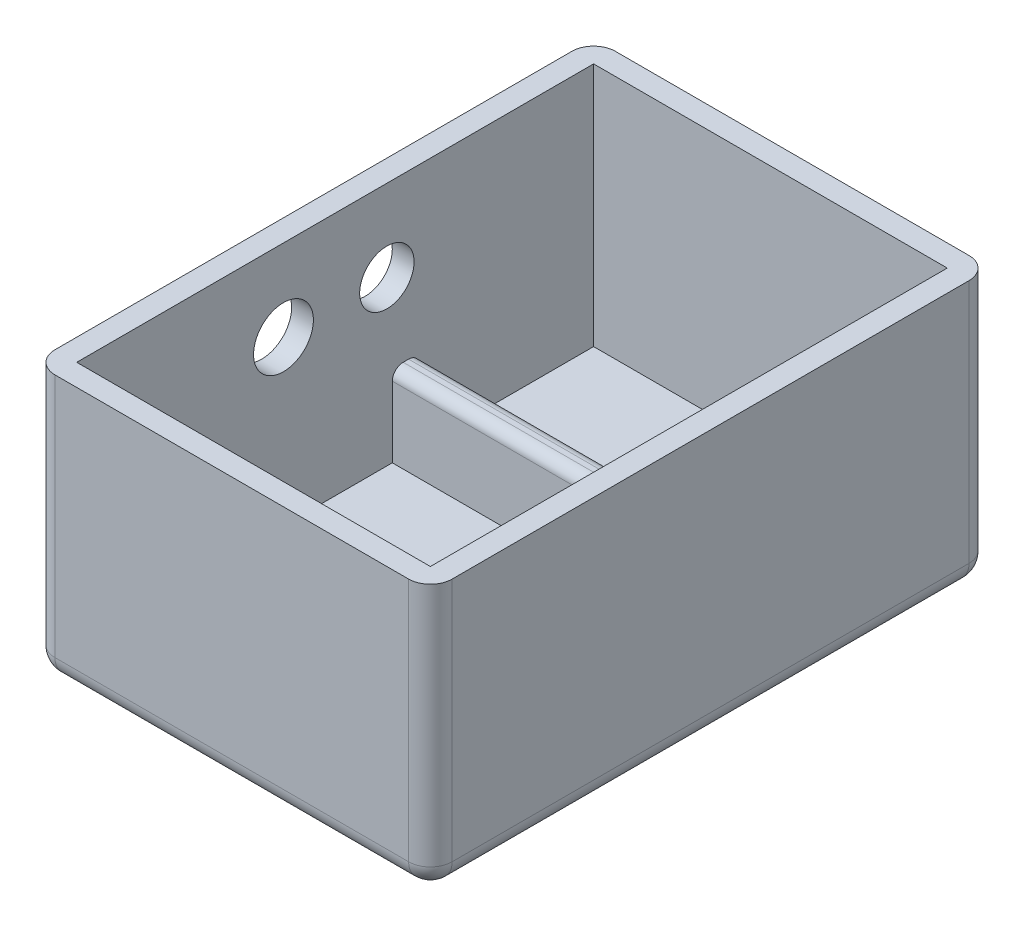
SolidWorks part; units mm, degrees
ref_plane "Front Plane" through (0, 0, 0) normal (0, 0, 1) x (1, 0, 0)
ref_plane "Top Plane" through (0, 0, 0) normal (0, 1, 0) x (1, 0, 0)
ref_plane "Right Plane" through (0, 0, 0) normal (1, 0, 0) x (0, 0, -1)
sketch "Sketch1" plane through (0, 0, 0) normal (0, 1, 0) x (1, 0, 0)
  line L1 (-32.5, -47.5) -> (32.5, -47.5)
  line L2 (-32.5, -47.5) -> (-32.5, 47.5)
  line L3 (-32.5, 47.5) -> (32.5, 47.5)
  line L4 (32.5, -47.5) -> (32.5, 47.5)
  line L5 (-32.5, -47.5) -> (32.5, 47.5) construction
  line L6 (-32.5, 47.5) -> (32.5, -47.5) construction
  point P0 (0, 0)
  dimension "D1" = 95
  dimension "D2" = 65
extrude "Boss-Extrude1" add sketch "Sketch1" along normal blind 45
shell "Shell4" thickness 4
sketch "Sketch3" plane through (0, 0, 0) normal (0, 1, 0) x (1, 0, 0)
  line L0 (-32.5, 47.5) -> (-32.5, -47.5) construction
  line L1 (-32.5, 15.5) -> (32.5, 15.5)
  line L2 (-32.5, 15.5) -> (-32.5, 10.5)
  line L3 (-32.5, 10.5) -> (32.5, 10.5)
  line L4 (32.5, 15.5) -> (32.5, 10.5)
  line L5 (32.5, -47.5) -> (32.5, 47.5) construction
  line L6 (-32.5, -47.5) -> (32.5, -47.5) construction
  dimension "D1" = 58
  dimension "D2" = 5
extrude "Boss-Extrude3" add sketch "Sketch3" along normal blind 15
sketch "Sketch4" plane through (-32.5, 0, 0) normal (1, 0, 0) x (0, 0, -1)
  line L0 (-47.5, 30) -> (47.5, 30) construction
  line L1 (-47.5, 45) -> (-47.5, 0) construction
  line L2 (47.5, 45) -> (47.5, 0) construction
  line L3 (47.5, 45) -> (-47.5, 45) construction
  circle A0 centre (9.5, 30) radius 5
  circle A1 centre (-9.5, 30) radius 5.5
  point P12 (-10.7969, 30)
  point P13 (5.9574, 30)
  point P16 (14.3271, 30.8945)
  dimension "D2" = 10
  dimension "D3" = 11
  dimension "D1" = 15
  dimension "D4" = 19
  dimension "D5" = 38
extrude "Cut-Extrude1" cut sketch "Sketch4" against normal blind 5
fillet "Fillet1" radius 4 8 edges at (-36.5, -4, 0) (0, -4, 51.5) (36.5, -4, 0) (0, -4, -51.5) (36.5, 20.5, -51.5) (-36.5, 20.5, -51.5) (-36.5, 20.5, 51.5) (36.5, 20.5, 51.5)
fillet "Fillet2" radius 2 2 edges at (0, 15, -10.5) (0, 15, -15.5)
